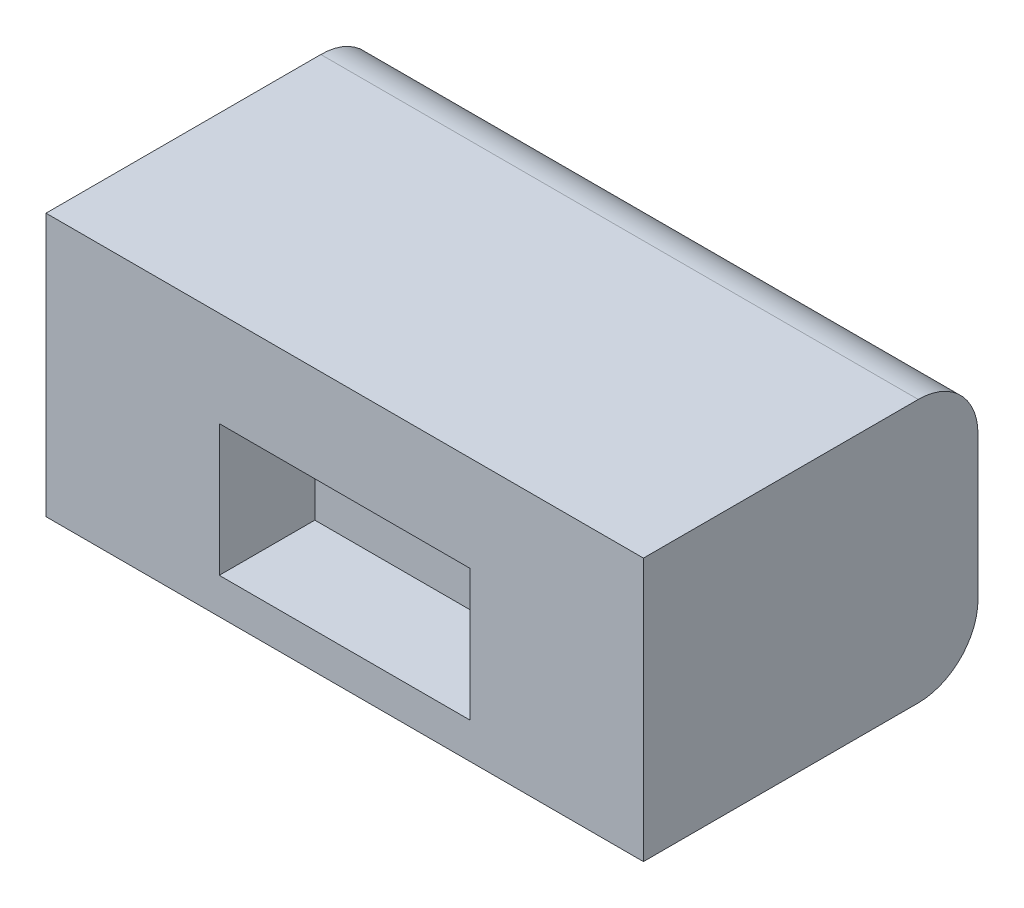
SolidWorks part; units mm, degrees
ref_plane "前视基准面" through (0, 0, 0) normal (0, 0, 1) x (1, 0, 0)
ref_plane "上视基准面" through (0, 0, 0) normal (0, 1, 0) x (1, 0, 0)
ref_plane "右视基准面" through (0, 0, 0) normal (1, 0, 0) x (0, 0, -1)
sketch "草图1" plane through (0, 0, 0) normal (0, 0, 1) x (1, 0, 0)
  line L1 (-2.5, 1.1) -> (2.5, 1.1)
  line L2 (-2.5, 1.1) -> (-2.5, -1.1)
  line L3 (-2.5, -1.1) -> (2.5, -1.1)
  line L4 (2.5, 1.1) -> (2.5, -1.1)
  line L5 (-2.5, 1.1) -> (2.5, -1.1) construction
  line L6 (-2.5, -1.1) -> (2.5, 1.1) construction
  point P0 (0, 0)
  dimension "D1" = 5
  dimension "D2" = 2.2
extrude "凸台-拉伸1" add sketch "草图1" along normal blind 2.8
sketch "草图2" plane through (0, 0, 2.8) normal (0, 0, 1) x (1, 0, 0)
  line L0 (-2.5, -1.1) -> (2.5, -1.1) construction
  line L1 (-1.05, 0.3) -> (1.05, 0.3)
  line L2 (-1.05, 0.3) -> (-1.05, -0.8)
  line L3 (-1.05, -0.8) -> (1.05, -0.8)
  line L4 (1.05, 0.3) -> (1.05, -0.8)
  line L5 (-1.05, 0.3) -> (1.05, -0.8) construction
  line L6 (-1.05, -0.8) -> (1.05, 0.3) construction
  point P0 (0, -0.25)
  dimension "D1" = 0.3
  dimension "D2" = 1.1
  dimension "D3" = 2.1
extrude "切除-拉伸1" cut sketch "草图2" against normal blind 0.8
fillet "圆角1" radius 0.5 2 edges at (0, -1.1, 0) (0, 1.1, 0)
